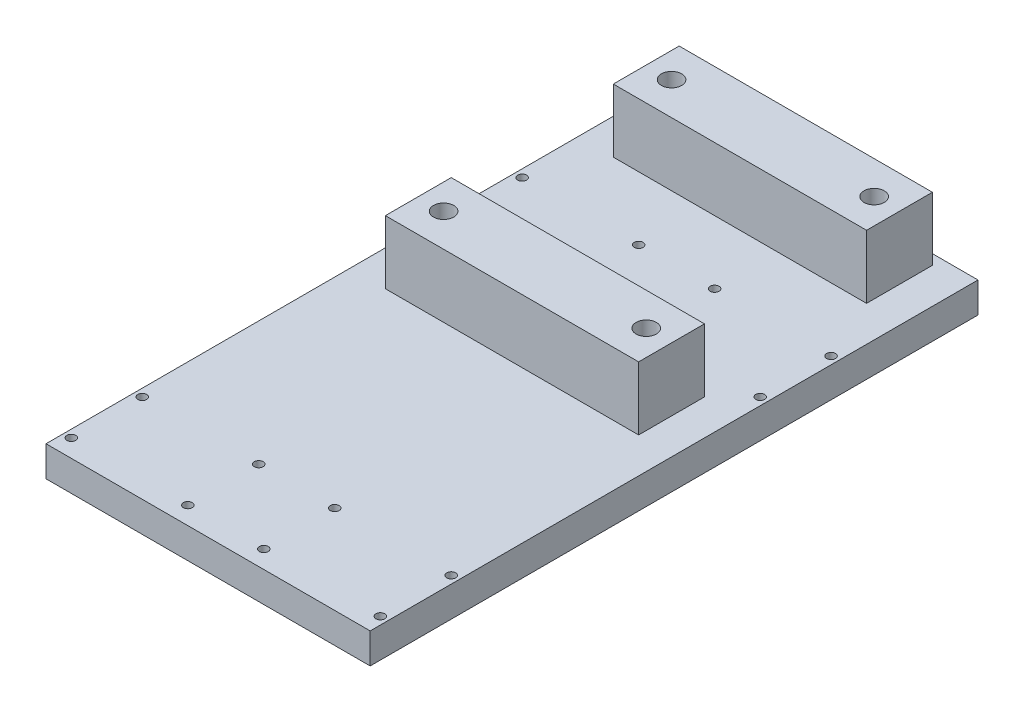
SolidWorks part; units mm, degrees
material "PW50:3:Ar:0:-1:C1:1:2:3:Re:11:"
ref_plane "front" through (0, 0, 0) normal (0, 0, 1) x (1, 0, 0)
ref_plane "top" through (0, 0, 0) normal (0, 1, 0) x (1, 0, 0)
ref_plane "side" through (0, 0, 0) normal (1, 0, 0) x (0, 0, -1)
sketch "Sketch1" plane through (0, 0, 0) normal (0, 1, 0) x (1, 0, 0)
  line L0 (0, 0) -> (0, -121.29) construction
  line L1 (-101.6, 0) -> (101.6, 0)
  line L2 (101.6, 0) -> (101.6, -381)
  line L3 (101.6, -381) -> (-101.6, -381)
  line L4 (-101.6, 0) -> (-101.6, -381)
  point P8 (0, 0)
  dimension "D1" = 381
  dimension "D2" = 203.2
extrude "Base-Extrude" add sketch "Sketch1" along normal blind 19.05
sketch "Sketch2" plane through (0, 19.05, 0) normal (0, 1, 0) x (-1, 0, 0)
  line L0 (79.375, 6.35) -> (-79.375, 6.35)
  line L1 (79.375, 6.35) -> (79.375, 47.625)
  line L2 (-79.375, 47.625) -> (79.375, 47.625)
  line L3 (-79.375, 47.625) -> (-79.375, 6.35)
  line L4 (0, 6.35) -> (0, 0) construction
  line L5 (101.6, 0) -> (-101.6, 0) construction
  dimension "D1" = 41.275
  dimension "D2" = 158.75
  dimension "D3" = 6.35
extrude "Boss-Extrude1" add sketch "Sketch2" along normal blind 39.6875
sketch "Sketch4" plane through (0, 58.7375, 0) normal (0, 1, 0) x (-1, 0, 0)
  line L0 (-79.375, 26.9875) -> (79.375, 26.9875) construction
  line L1 (-79.375, 47.625) -> (-79.375, 6.35) construction
  line L2 (79.375, 6.35) -> (79.375, 47.625) construction
  line L3 (0, 26.9875) -> (0, 42.4643) construction
  circle A0 centre (-63.5, 26.9875) radius 6.35
  circle A1 centre (63.5, 26.9875) radius 6.35
  dimension "D1" = 12.7
  dimension "D2" = 127
extrude "Cut-Extrude1" cut sketch "Sketch4" against normal blind 38.1
pattern_linear "LPattern1" count 2 spacing 142.875 along (0, 0, 1) of "Boss-Extrude1", "Cut-Extrude1"
ref_plane "Plane4" through (0, 0, 26.9875) normal (0, 0, 1) x (1, 0, 0)
sketch "Sketch5" plane through (0, 0, 0) normal (0, -1, 0) x (1, 0, 0)
  line L0 (96.8375, 369.8875) -> (-96.8375, 369.8875) construction
  line L1 (96.8375, 369.8875) -> (96.8375, 87.3125) construction
  line L2 (96.8375, 87.3125) -> (-96.8375, 87.3125) construction
  line L3 (-96.8375, 87.3125) -> (-96.8375, 369.8875) construction
  line L4 (-96.8375, 325.4375) -> (96.8375, 325.4375) construction
  line L5 (-96.8375, 131.7625) -> (96.8375, 131.7625) construction
  line L7 (101.6, 381) -> (-101.6, 381) construction
  line L8 (-101.6, 0) -> (-101.6, 381) construction
  line L9 (23.8125, 369.8875) -> (23.8125, 87.3125) construction
  line L10 (-23.8125, 369.8875) -> (-23.8125, 87.3125) construction
  circle A4 centre (96.8375, 87.3125) radius 2.7781
  circle A5 centre (96.8375, 131.7625) radius 2.7781
  circle A6 centre (96.8375, 369.8875) radius 2.7781
  circle A7 centre (96.8375, 325.4375) radius 2.7781
  circle A10 centre (23.8125, 87.3125) radius 2.7781
  circle A11 centre (23.8125, 131.7625) radius 2.7781
  circle A16 centre (-96.8375, 325.4375) radius 2.7781
  circle A17 centre (-96.8375, 369.8875) radius 2.7781
  circle A18 centre (-23.8125, 369.8875) radius 2.7781
  circle A19 centre (-23.8125, 325.4375) radius 2.7781
  circle A24 centre (-96.8375, 87.3125) radius 2.7781
  circle A25 centre (-96.8375, 131.7625) radius 2.7781
  circle A26 centre (-23.8125, 131.7625) radius 2.7781
  circle A27 centre (-23.8125, 87.3125) radius 2.7781
  circle A30 centre (23.8125, 369.8875) radius 2.7781
  circle A31 centre (23.8125, 325.4375) radius 2.7781
  dimension "D7" = 5.5562
  dimension "D1" = 11.1125
  dimension "D2" = 4.7625
  dimension "D3" = 44.45
  dimension "D4" = 73.025
  dimension "D5" = 120.65
  dimension "D6" = 73.025
  dimension "D8" = 44.45
  dimension "D9" = 238.125
  dimension "D10" = 44.45
extrude "Cut-Extrude2" cut sketch "Sketch5" against normal through all
